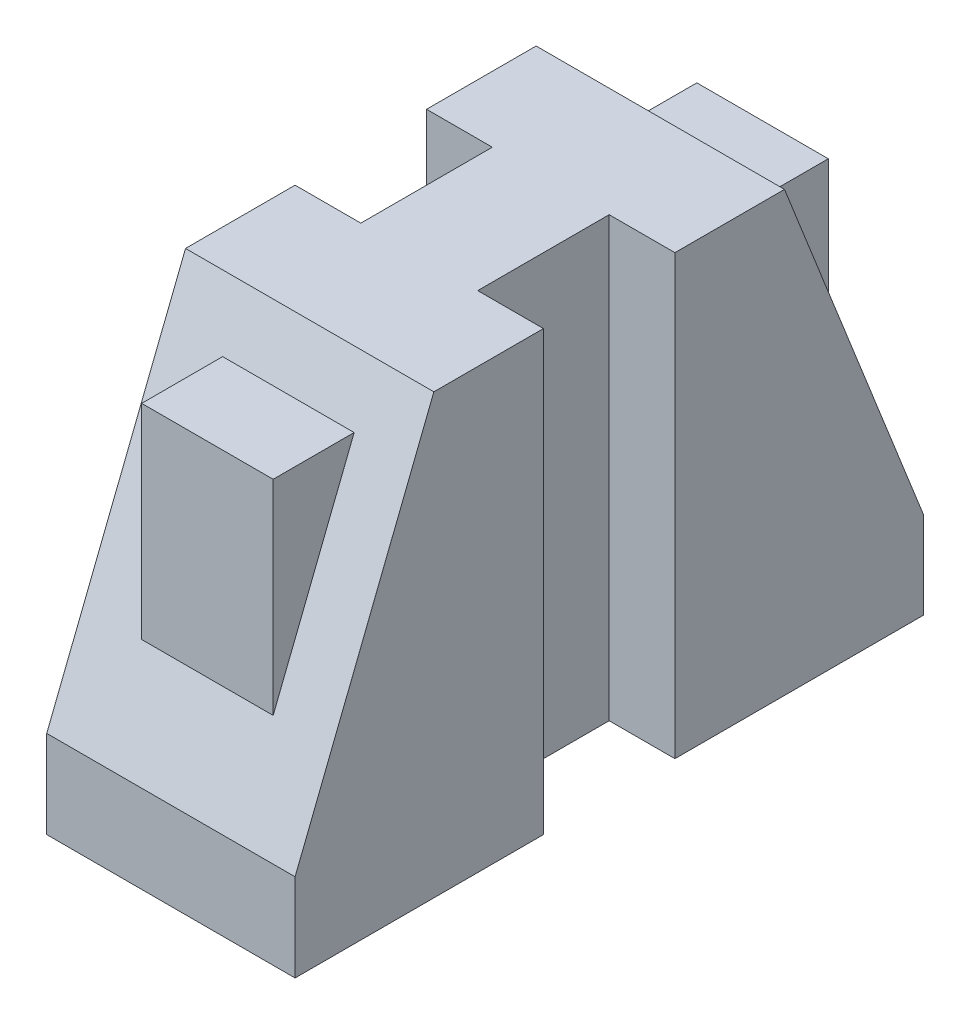
SolidWorks part; units mm, degrees
ref_plane "Alzado" through (0, 0, 0) normal (0, 0, 1) x (1, 0, 0)
ref_plane "Planta" through (0, 0, 0) normal (0, 1, 0) x (1, 0, 0)
ref_plane "Vista lateral" through (0, 0, 0) normal (1, 0, 0) x (0, 0, -1)
sketch "Croquis1" plane through (0, 0, 0) normal (1, 0, 0) x (0, 0, -1)
  line L0 (0, 0) -> (0, 60) construction
  line L1 (43, 0) -> (-43, 0)
  line L2 (-43, 0) -> (-43, 12)
  line L3 (-43, 12) -> (-24, 60)
  line L4 (-24, 60) -> (24, 60)
  line L5 (43, 0) -> (43, 12)
  line L6 (43, 12) -> (24, 60)
  dimension "D1" = 86
  dimension "D2" = 12
  dimension "D3" = 60
  dimension "D4" = 48
extrude "Saliente-Extruir2" add sketch "Croquis1" along normal mid plane 34
sketch "Croquis2" plane through (0, 60, 0) normal (0, 1, 0) x (1, 0, 0)
  line L0 (17, 24) -> (17, -24) construction
  line L1 (17, 9) -> (8, 9)
  line L2 (17, 9) -> (17, -9)
  line L3 (17, -9) -> (8, -9)
  line L4 (8, 9) -> (8, -9)
  line L5 (0, 0) -> (0, 21.0332) construction
  line L6 (-17, 9) -> (-8, 9)
  line L7 (-8, 9) -> (-8, -9)
  line L8 (-17, -9) -> (-8, -9)
  line L9 (-17, 9) -> (-17, -9)
  line L10 (17, -24) -> (-17, -24) construction
  point P16 (-17, 0)
  dimension "D1" = 15
  dimension "D2" = 16
extrude "Cortar-Extruir1" cut sketch "Croquis2" against normal through all
sketch "Croquis3" plane through (0, 0, 0) normal (1, 0, 0) x (0, 0, -1)
  line L0 (-38, 24.6316) -> (-38, 52.6316)
  line L1 (-24, 60) -> (-43, 12) construction
  line L2 (-38, 52.6316) -> (-26.9167, 52.6316)
  line L3 (0, 0) -> (0, 57.1347) construction
  line L4 (9, 0) -> (-9, 0) construction
  line L5 (-26.9167, 52.6316) -> (-38, 24.6316)
  line L6 (26.9167, 52.6316) -> (38, 24.6316)
  line L7 (38, 52.6316) -> (26.9167, 52.6316)
  line L8 (38, 24.6316) -> (38, 52.6316)
  dimension "D1" = 28
  dimension "D2" = 76
extrude "Saliente-Extruir3" add sketch "Croquis3" along normal mid plane 18
